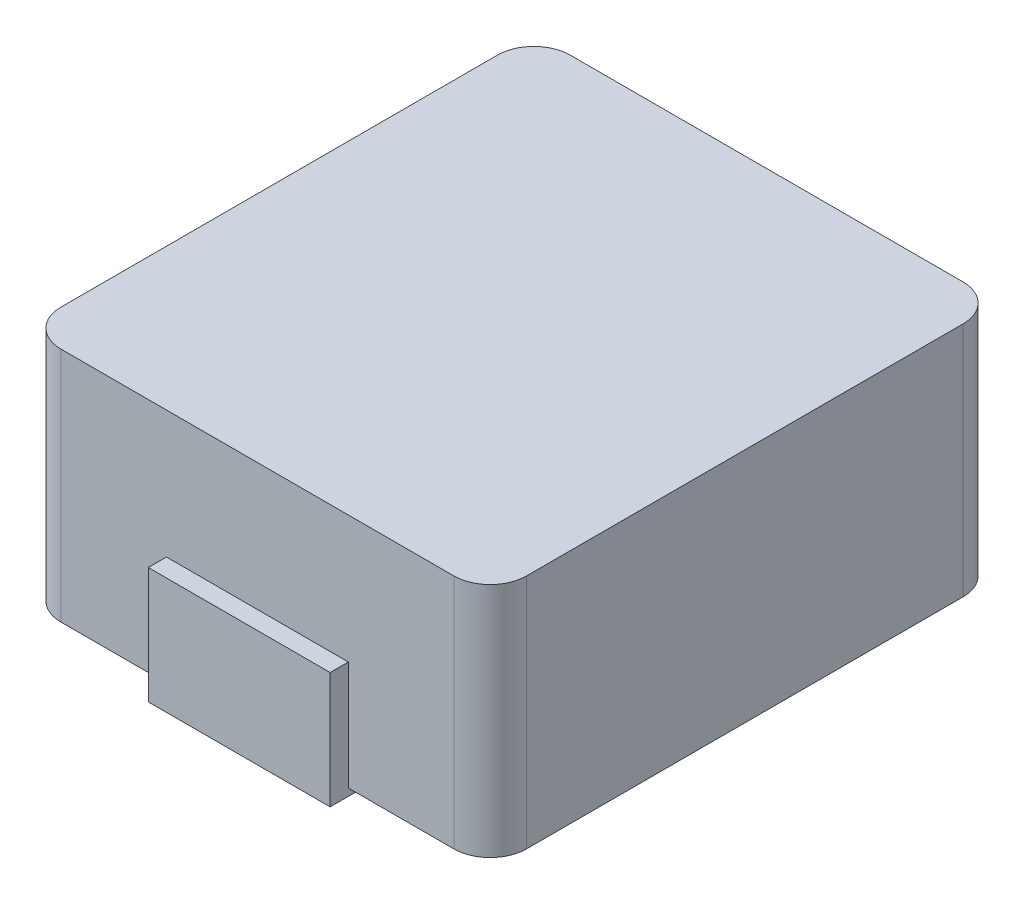
SolidWorks part; units mm, degrees
ref_plane "Front Plane" through (0, 0, 0) normal (0, 0, 1) x (1, 0, 0)
ref_plane "Top Plane" through (0, 0, 0) normal (0, 1, 0) x (1, 0, 0)
ref_plane "Right Plane" through (0, 0, 0) normal (1, 0, 0) x (0, 0, -1)
sketch "Sketch1" plane through (0, 0, 0) normal (0, 1, 0) x (1, 0, 0)
  line L0 (0, 0) -> (0, 14)
  line L1 (0, 14) -> (12.8, 14)
  line L2 (0, 0) -> (12.8, 0)
  line L3 (12.8, 0) -> (12.8, 14)
extrude "Boss-Extrude1" add sketch "Sketch1" along normal blind 6.5
fillet "Fillet1" radius 1 4 edges at (0, 3.25, -14) (0, 3.25, 0) (12.8, 3.25, -14) (12.8, 3.25, 0)
sketch "Sketch2" plane through (0, 0, 0) normal (0, -1, 0) x (1, 0, 0)
  line L1 (1, 0) -> (11.8, 0) construction
  line L2 (8.9, 0) -> (8.9, -2.6)
  line L3 (8.9, 0) -> (8.9, 0.5)
  line L4 (8.9, -2.6) -> (3.9, -2.6)
  line L5 (3.9, -2.6) -> (3.9, 0.5)
  line L6 (3.9, 0.5) -> (8.9, 0.5)
  line L9 (3.9, -14.5) -> (8.9, -14.5)
  line L10 (3.9, -11.4) -> (3.9, -14.5)
  line L11 (8.9, -11.4) -> (3.9, -11.4)
  line L12 (8.9, -14) -> (8.9, -14.5)
  line L13 (8.9, -14) -> (8.9, -11.4)
extrude "Boss-Extrude2" add sketch "Sketch2" along normal blind 0.2 and the other way blind 3
